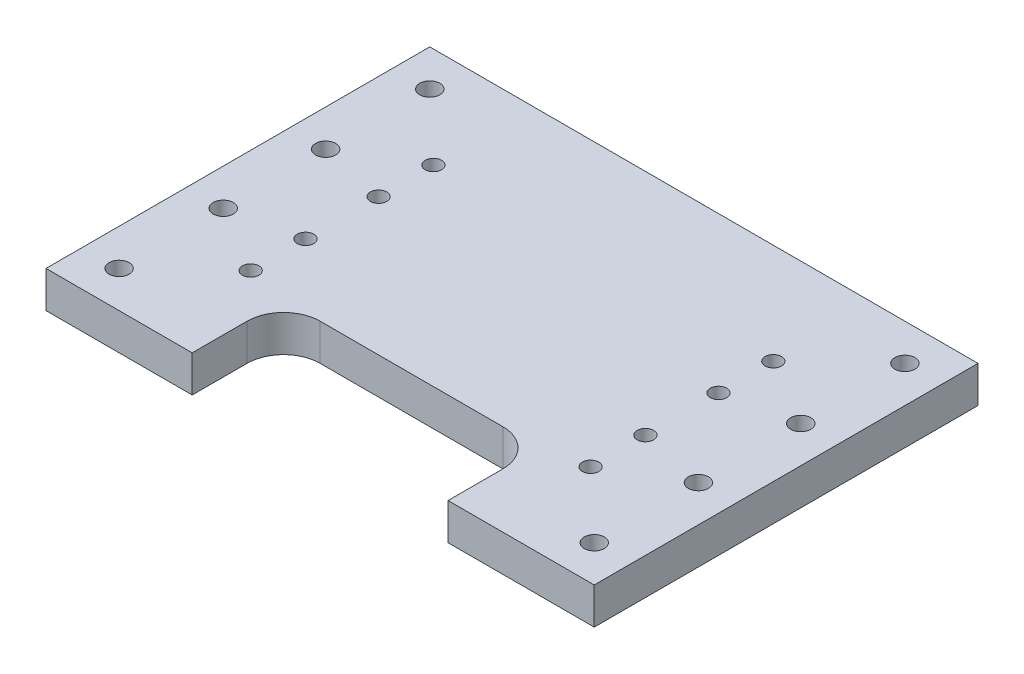
SolidWorks part; units mm, degrees
material "ALUMINIUM,  6082-T6"
ref_plane "Front Plane" through (0, 0, 0) normal (0, 0, 1) x (1, 0, 0)
ref_plane "Top Plane" through (0, 0, 0) normal (0, 1, 0) x (1, 0, 0)
ref_plane "Right Plane" through (0, 0, 0) normal (1, 0, 0) x (0, 0, -1)
sketch "Sketch1" plane through (0, 0, 0) normal (0, 1, 0) x (1, 0, 0)
  line L0 (-75, 52.5) -> (75, -52.5) construction
  line L1 (75, 52.5) -> (-75, 52.5)
  line L2 (75, 52.5) -> (75, -52.5)
  line L3 (75, -52.5) -> (-75, -52.5)
  line L4 (-75, 52.5) -> (-75, -52.5)
  dimension "D1" = 150
  dimension "D2" = 105
extrude "Boss-Extrude1" add sketch "Sketch1" along normal mid plane 10
hole_wizard "CBORE for M4 Hex Socket Head Cap Screw1" positions "Sketch2" profile "Sketch3" counterbore size "M4" standard "ISO" end condition through all
sketch "Sketch2" plane through (0, -5, 0) normal (0, -1, 0) x (-1, 0, 0)
  line L0 (-46.5, -25) -> (-46.5, -10) construction
  line L1 (-46.5, -10) -> (-46.5, 10) construction
  line L2 (-46.5, 10) -> (-46.5, 25) construction
  line L3 (46.5, -25) -> (46.5, -10) construction
  line L4 (46.5, -10) -> (46.5, 10) construction
  line L5 (46.5, 10) -> (46.5, 25) construction
  line L7 (-46.5, 25) -> (46.5, 25) construction
  line L10 (46.5, -25) -> (-46.5, -25) construction
  line L13 (-46.5, -10) -> (46.5, -10) construction
  line L16 (46.5, 10) -> (-46.5, 10) construction
  line L17 (-46.5, 10) -> (46.5, -10) construction
  point P3 (-46.5, -25)
  point P4 (-46.5, -10)
  point P5 (-46.5, 10)
  point P6 (-46.5, 25)
  point P13 (46.5, -25)
  point P14 (46.5, -10)
  point P15 (46.5, 10)
  point P16 (46.5, 25)
  dimension "D1" = 15
  dimension "D2" = 20
  dimension "D3" = 93
sketch "Sketch3" plane through (46.5, -5, 25) normal (1, 0, 0) x (0, 0, -1)
  line L0 (0, 0) -> (0, 10)
  line L1 (0, 10) -> (2.25, 10)
  line L3 (2.25, 10) -> (2.25, 4.5)
  line L4 (2.25, 4.5) -> (4, 4.5)
  line L5 (4, 4.5) -> (4, 0)
  line L7 (4, 0) -> (0, 0)
  line L11 (0, -6.35) -> (0, 107.95) construction
  dimension "Thru Hole Dia." = 4.5
  dimension "Thru Hole Depth" = 10
  dimension "C'Bore Dia." = 8
  dimension "C'Bore Depth" = 4.5
hole_wizard "Ø5.5 (5.5) Diameter Hole1" positions "Sketch7" profile "Sketch8" hole size "Ø5.5" standard "ISO" end condition through all
sketch "Sketch7" plane through (0, 5, 0) normal (0, 1, 0) x (1, 0, 0)
  line L0 (-65, 42.5) -> (65, 42.5) construction
  line L1 (65, 42.5) -> (65, -42.5) construction
  line L2 (65, -42.5) -> (-65, -42.5) construction
  line L3 (-65, -42.5) -> (-65, 42.5) construction
  line L4 (-65, 42.5) -> (65, -42.5) construction
  line L6 (-65, -14) -> (65, 14) construction
  line L8 (-65, -14) -> (65, -14) construction
  line L11 (65, 14) -> (-65, 14) construction
  line L13 (-75, 52.5) -> (-75, -52.5) construction
  line L14 (75, 52.5) -> (-75, 52.5) construction
  point P0 (65, -42.5)
  point P2 (65, 42.5)
  point P4 (-65, 42.5)
  point P6 (-65, -42.5)
  point P8 (-65, -14)
  point P10 (65, -14)
  point P12 (-65, 14)
  point P14 (65, 14)
  dimension "D1" = 10
  dimension "D2" = 10
  dimension "D3" = 28
  dimension "D4" = 28.5
sketch "Sketch8" plane through (65, 5, 42.5) normal (1, 0, 0) x (0, 0, 1)
  line L0 (0, 0) -> (0, 10)
  line L1 (0, 10) -> (2.75, 10)
  line L2 (2.75, 10) -> (2.75, 0)
  line L5 (2.75, 0) -> (0, 0)
  line L11 (0, -6.35) -> (0, 107.95) construction
  dimension "Thru Hole Dia." = 5.5
  dimension "Thru Hole Depth" = 10
sketch "Sketch9" plane through (0, 5, 0) normal (0, 1, 0) x (1, 0, 0)
  line L0 (0, 0) -> (0, -27.5) construction
  line L1 (-35, -52.5) -> (35, -52.5)
  line L2 (-35, -52.5) -> (-35, -27.5)
  line L3 (-35, -27.5) -> (35, -27.5)
  line L4 (35, -52.5) -> (35, -27.5)
  line L5 (-75, -52.5) -> (75, -52.5) construction
  dimension "D1" = 25
  dimension "D2" = 70
extrude "Cut-Extrude1" cut sketch "Sketch9" against normal blind 10
fillet "Fillet1" radius 10 2 edges at (-35, 0, 27.5) (35, 0, 27.5)
